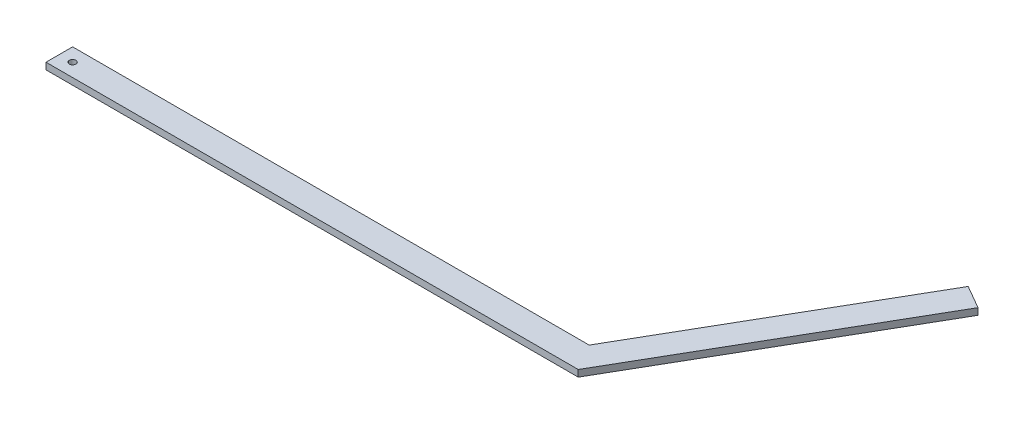
SolidWorks part; units mm, degrees
ref_plane "Front Plane" through (0, 0, 0) normal (0, 0, 1) x (1, 0, 0)
ref_plane "Top Plane" through (0, 0, 0) normal (0, 1, 0) x (1, 0, 0)
ref_plane "Right Plane" through (0, 0, 0) normal (1, 0, 0) x (0, 0, -1)
sketch "Sketch1" plane through (0, 0, 0) normal (0, 1, 0) x (1, 0, 0)
  line L0 (508, 0) -> (647.6683, 241.9126)
  line L1 (508, 0) -> (0, 0)
  line L2 (0, 0) -> (0, 25.4)
  line L3 (0, 25.4) -> (493.0572, 25.4)
  line L4 (647.6683, 241.9126) -> (625.4626, 254.733)
  line L5 (625.4626, 254.733) -> (493.0572, 25.4)
  dimension "D1" = 25.4
  dimension "D2" = 508
  dimension "D3" = 120
extrude "Boss-Extrude1" add sketch "Sketch1" along normal blind 6.35
sketch "Sketch2" plane through (0, 6.35, 0) normal (0, 1, 0) x (1, 0, 0)
  line L0 (0, 25.4) -> (0, 0) construction
  line L1 (493.0572, 25.4) -> (0, 25.4) construction
  circle A0 centre (12.7, 12.7) radius 3.175
  dimension "D1" = 6.35
  dimension "D2" = 12.7
  dimension "D3" = 12.7
extrude "Cut-Extrude1" cut sketch "Sketch2" against normal blind 6.35
